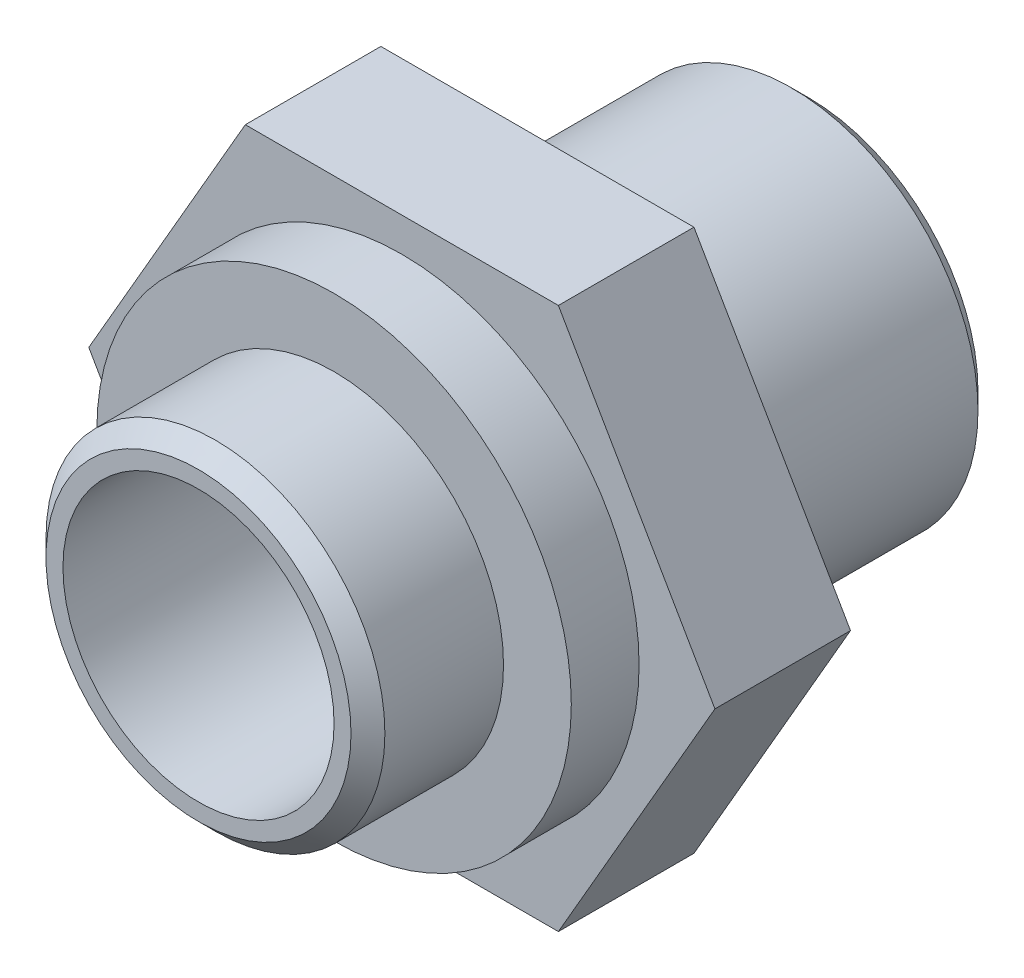
SolidWorks part; units mm, degrees
ref_plane "Front Plane" through (0, 0, 0) normal (0, 0, 1) x (1, 0, 0)
ref_plane "Top Plane" through (0, 0, 0) normal (0, 1, 0) x (1, 0, 0)
ref_plane "Right Plane" through (0, 0, 0) normal (1, 0, 0) x (0, 0, -1)
sketch "Sketch2" plane through (0, 0, 0) normal (0, 0, 1) x (1, 0, 0)
  circle A0 centre (0, 0) radius 2.75
  dimension "D1" = 5.5
extrude "Boss-Extrude1" add sketch "Sketch2" along normal blind 4
sketch "Sketch3" plane through (0, 0, 4) normal (0, 0, 1) x (1, 0, 0)
  line L1 (4.6188, 0) -> (2.3094, 4)
  line L2 (2.3094, 4) -> (-2.3094, 4)
  line L3 (-2.3094, 4) -> (-4.6188, 0)
  line L4 (-4.6188, 0) -> (-2.3094, -4)
  line L5 (-2.3094, -4) -> (2.3094, -4)
  line L6 (2.3094, -4) -> (4.6188, 0)
  circle A0 centre (0, 0) radius 4 construction
  dimension "D1" = 8
extrude "Boss-Extrude2" add sketch "Sketch3" along normal blind 2
sketch "Sketch4" plane through (0, 0, 6) normal (0, 0, 1) x (1, 0, 0)
  circle A0 centre (0, 0) radius 3.5
  dimension "D1" = 7
extrude "Boss-Extrude3" add sketch "Sketch4" along normal blind 1
sketch "Sketch5" plane through (0, 0, 7) normal (0, 0, 1) x (1, 0, 0)
  circle A0 centre (0, 0) radius 2.5
  circle A1 centre (0, 0) radius 3.5 construction
  dimension "D1" = 5
extrude "Boss-Extrude5" add sketch "Sketch5" along normal blind 2
sketch "Sketch7" plane through (0, 0, 9) normal (0, 0, 1) x (1, 0, 0)
  circle A0 centre (0, 0) radius 2
  dimension "D1" = 4
extrude "Cut-Extrude1" cut sketch "Sketch7" against normal through all
chamfer "Chamfer1" distance 0.25 angle 45 2 edges at (2.75, 0, 0) (2.5, 0, 9)
